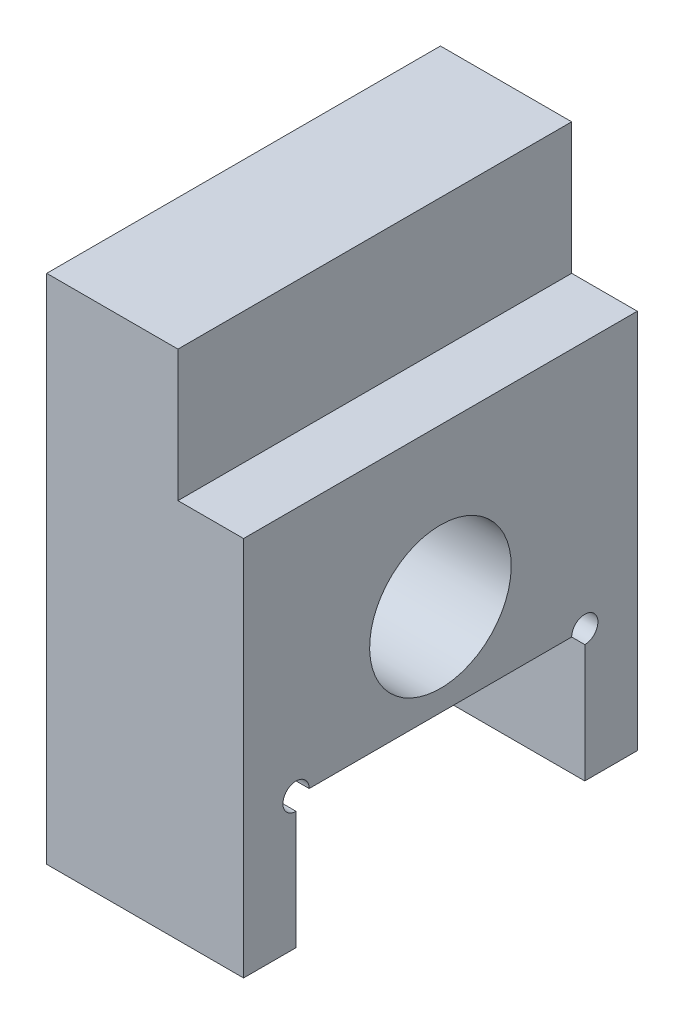
SolidWorks part; units mm, degrees
material "AISI 1045 Aço, trefilado"
ref_plane "Plano frontal" through (0, 0, 0) normal (0, 0, 1) x (1, 0, 0)
ref_plane "Plano superior" through (0, 0, 0) normal (0, 1, 0) x (1, 0, 0)
ref_plane "Plano direito" through (0, 0, 0) normal (1, 0, 0) x (0, 0, -1)
sketch "Esboço1" plane through (0, 0, 0) normal (0, 0, 1) x (1, 0, 0)
  line L0 (0, 0) -> (0, -39)
  line L1 (0, -39) -> (15, -39)
  line L2 (15, -39) -> (15, -10)
  line L3 (15, -10) -> (10, -10)
  line L4 (10, -10) -> (10, 0)
  line L5 (10, 0) -> (0, 0)
  dimension "D1" = 39
  dimension "D2" = 15
  dimension "D3" = 5
  dimension "D4" = 10
extrude "Ressalto-extrusão1" add sketch "Esboço1" along normal blind 30
sketch "Esboço2" plane through (15, 0, 0) normal (1, 0, 0) x (0, 0, -1)
  line L0 (-30, -39) -> (0, -39) construction
  line L1 (-26, -39) -> (-4, -39)
  line L2 (-26, -39) -> (-26, -29)
  line L3 (-26, -29) -> (-4, -29)
  line L4 (-4, -39) -> (-4, -29)
  dimension "D1" = 22
  dimension "D2" = 4
  dimension "D3" = 10
extrude "Corte-extrusão1" cut sketch "Esboço2" against normal through all
sketch "Esboço3" plane through (15, 0, 0) normal (1, 0, 0) x (0, 0, -1)
  circle A0 centre (-26, -29) radius 1
  circle A1 centre (-4, -29) radius 1
  dimension "D1" = 2
  dimension "D2" = 2
extrude "Corte-extrusão2" cut sketch "Esboço3" against normal through all
sketch "Esboço4" plane through (15, 0, 0) normal (1, 0, 0) x (0, 0, -1)
  line L0 (0, -39) -> (0, -10) construction
  circle A0 centre (-15, -22) radius 5.395
  dimension "D1" = 10.79
  dimension "D2" = 17
  dimension "D3" = 15
extrude "Corte-extrusão3" cut sketch "Esboço4" against normal through all
